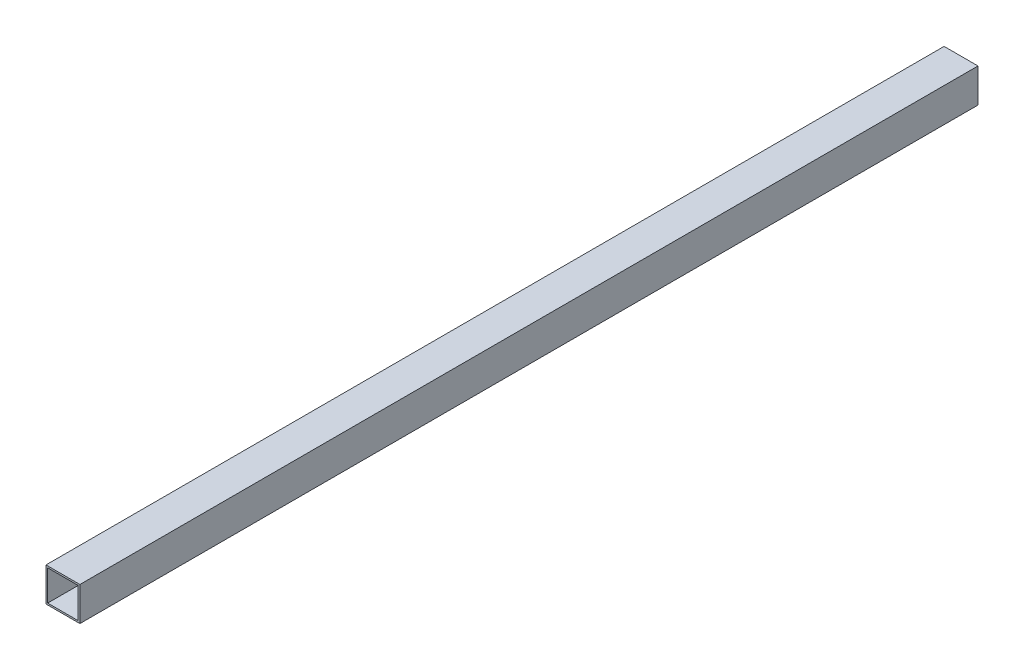
SolidWorks part; units mm, degrees
material "2024-O"
ref_plane "Alzado" through (0, 0, 0) normal (0, 0, 1) x (1, 0, 0)
ref_plane "Planta" through (0, 0, 0) normal (0, 1, 0) x (1, 0, 0)
ref_plane "Vista lateral" through (0, 0, 0) normal (1, 0, 0) x (0, 0, -1)
sketch "Croquis1" plane through (0, 0, 0) normal (0, 0, 1) x (1, 0, 0)
  line L1 (20, -20) -> (-20, -20)
  line L2 (20, -20) -> (20, 20)
  line L3 (20, 20) -> (-20, 20)
  line L4 (-20, -20) -> (-20, 20)
  line L5 (20, -20) -> (-20, 20) construction
  line L6 (20, 20) -> (-20, -20) construction
  point P0 (0, 0)
  dimension "D1" = 40
  dimension "D2" = 40
extrude "Extruir-Lámina1" add sketch "Croquis1" along normal blind 1060 thin
